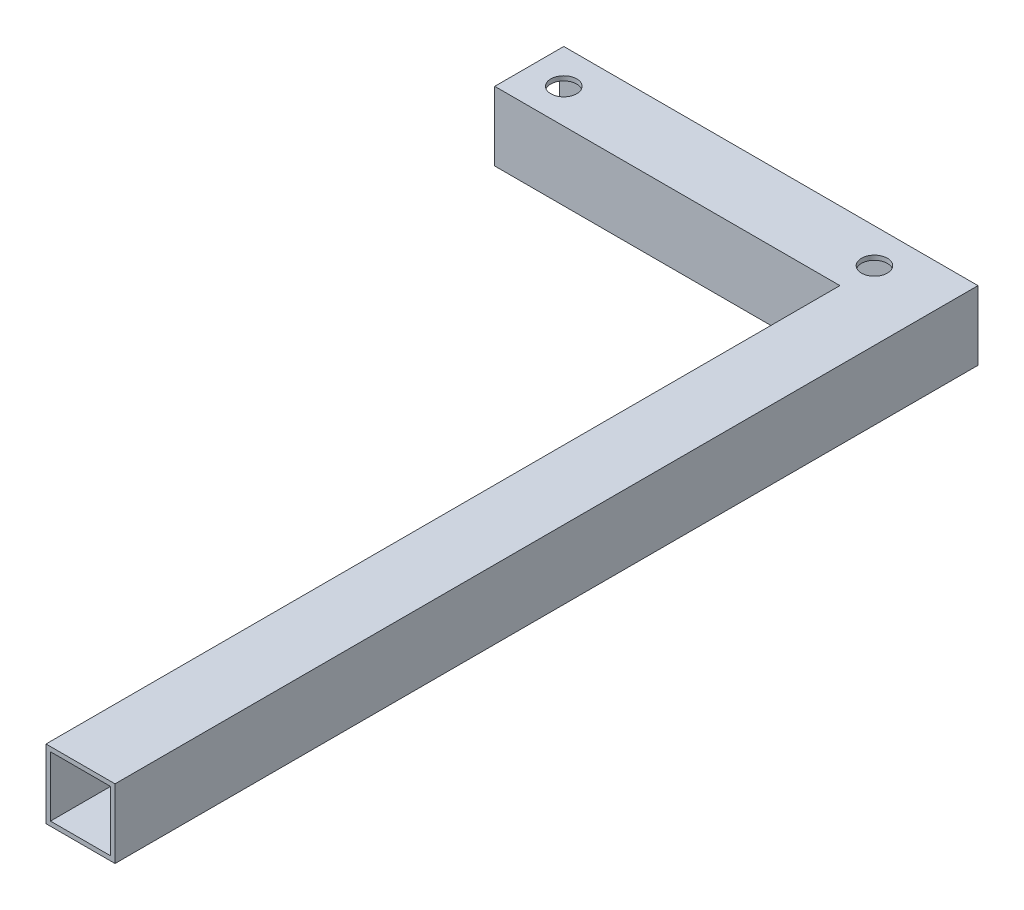
SolidWorks part; units mm, degrees
material "6061-T6 (SS)"
ref_plane "Front Plane" through (0, 0, 0) normal (0, 0, 1) x (1, 0, 0)
ref_plane "Top Plane" through (0, 0, 0) normal (0, 1, 0) x (1, 0, 0)
ref_plane "Right Plane" through (0, 0, 0) normal (1, 0, 0) x (0, 0, -1)
sketch "Sketch1" plane through (0, 0, 0) normal (0, 1, 0) x (1, 0, 0)
  line L0 (0, -13.97) -> (0, 13.97) construction
  line L1 (-12.7, 12.7) -> (139.7, 12.7)
  line L2 (-12.7, 12.7) -> (-12.7, -12.7)
  line L3 (-12.7, -12.7) -> (114.3, -12.7)
  line L6 (139.7, 12.7) -> (139.7, -304.8)
  line L7 (139.7, -304.8) -> (114.3, -304.8)
  line L8 (114.3, -12.7) -> (114.3, -304.8)
  line L9 (-13.97, 0) -> (13.97, 0) construction
  circle A0 centre (0, 0) radius 4.7625
  circle A1 centre (114.3, 0) radius 4.7625
  dimension "D7" = 9.525
  dimension "D1" = 25.4
  dimension "D2" = 25.4
  dimension "D3" = 12.7
  dimension "D4" = 114.3
  dimension "D5" = 12.7
  dimension "D6" = 292.1
  dimension "D8" = 114.3
extrude "Boss-Extrude1" add sketch "Sketch1" along normal mid plane 25.4
shell "Shell1" thickness 1.651
